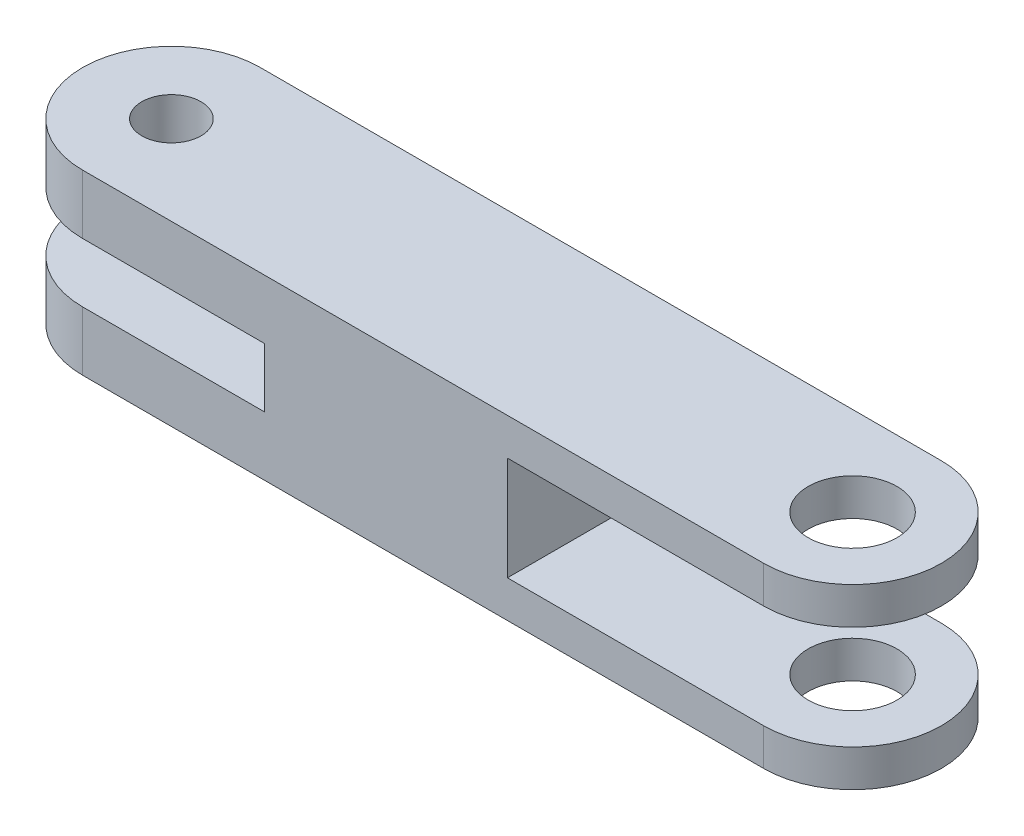
SolidWorks part; units mm, degrees
ref_plane "前视基准面" through (0, 0, 0) normal (0, 0, 1) x (1, 0, 0)
ref_plane "上视基准面" through (0, 0, 0) normal (0, 1, 0) x (1, 0, 0)
ref_plane "右视基准面" through (0, 0, 0) normal (1, 0, 0) x (0, 0, -1)
other "Configuration Table"
sketch "草图1" plane through (0, 0, 0) normal (0, 1, 0) x (1, 0, 0)
  line L0 (0, 0) -> (1, 0) construction
  line L1 (21.5, 0) -> (23, 0) construction
  line L2 (0, 3) -> (23, 3)
  line L3 (0, -3) -> (23, -3)
  arc A0 (0, 3) -> (0, -3) centre (0, 0) ccw
  arc A1 (23, -3) -> (23, 3) centre (23, 0) ccw
  circle A2 centre (23, 0) radius 1.5
  circle A3 centre (0, 0) radius 1
  point P3 (20, 0)
  dimension "D2" = 3
  dimension "D3" = 3
  dimension "D4" = 2
  dimension "D1" = 23
extrude "凸台-拉伸1" add sketch "草图1" along normal mid plane 6
sketch "草图6" plane through (0, 0, 0) normal (0, 1, 0) x (1, 0, 0)
  line L0 (14.3461, 7.8432) -> (14.3461, -3.762)
  line L1 (14.3461, -3.762) -> (45.8575, -3.762)
  line L2 (45.8575, -3.762) -> (45.8575, 7.8432)
  line L3 (45.8575, 7.8432) -> (14.3461, 7.8432)
extrude "切除-拉伸2" cut sketch "草图6" against normal mid plane 3.5
sketch "草图7" plane through (0, 0, 0) normal (0, 1, 0) x (1, 0, 0)
  line L0 (6.139, 5.0358) -> (6.139, -4.6141)
  line L1 (6.139, -4.6141) -> (-6.5212, -4.6141)
  line L2 (-6.5212, -4.6141) -> (-6.5212, 5.0358)
  line L3 (-6.5212, 5.0358) -> (6.139, 5.0358)
extrude "切除-拉伸3" cut sketch "草图7" against normal mid plane 2
